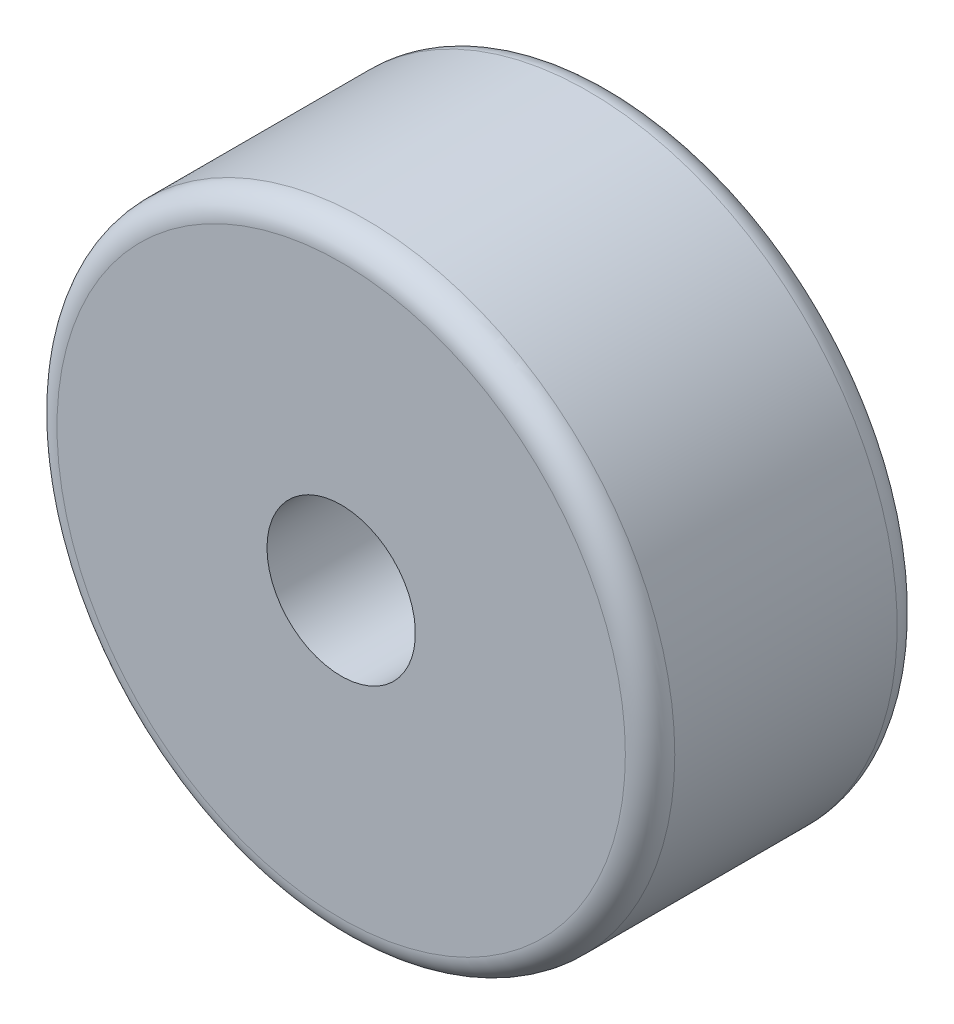
SolidWorks part; units mm, degrees
material "6061-T6 (SS)"
ref_plane "Front Plane" through (0, 0, 0) normal (0, 0, 1) x (1, 0, 0)
ref_plane "Top Plane" through (0, 0, 0) normal (0, 1, 0) x (1, 0, 0)
ref_plane "Right Plane" through (0, 0, 0) normal (1, 0, 0) x (0, 0, -1)
sketch "Sketch1" plane through (0, 0, 0) normal (1, 0, 0) x (0, 0, -1)
  line L0 (0, 0) -> (-53700.1768, 0) construction
  line L1 (-27.94, 15.2527) -> (-27.94, 63.5)
  line L2 (-27.94, 63.5) -> (27.94, 63.5)
  line L3 (27.94, 63.5) -> (27.94, 15.2527)
  line L4 (-27.94, 15.2527) -> (27.94, 15.2527)
  point P5 (0, 63.5)
  dimension "D1" = 55.88
  dimension "D2" = 127
  dimension "D3" = 30.5054
revolve "Revolve1" add sketch "Sketch1" angle 360 about L0
sketch "Sketch2" [suppressed] plane through (0, 0, 0) normal (1, 0, 0) x (0, 0, -1)
  line L0 (-25.4, 0) -> (25.4, 0) construction
  line L1 (-25.4, 63.5) -> (-25.4, -63.5) construction
  line L2 (25.4, -63.5) -> (25.4, 63.5) construction
  line L3 (25.4, 63.5) -> (-25.4, 63.5) construction
  line L4 (16.51, 63.5) -> (25.4, 63.5)
  line L5 (16.51, 63.5) -> (16.51, 0)
  line L6 (16.51, 0) -> (25.4, 0)
  line L7 (25.4, 63.5) -> (25.4, 0)
  line L8 (16.51, 63.5) -> (25.4, 0) construction
  line L9 (16.51, 0) -> (25.4, 63.5) construction
  point P10 (20.955, 31.75)
  dimension "D1" = 41.91
revolve "Cut-Revolve1" [suppressed] cut sketch "Sketch2" angle 360 about L0
fillet "Fillet1" radius 5.08 2 edges at (-63.5, 0, -27.94) (-63.5, 0, 27.94)
fillet "Fillet2" [suppressed] radius 5.08
